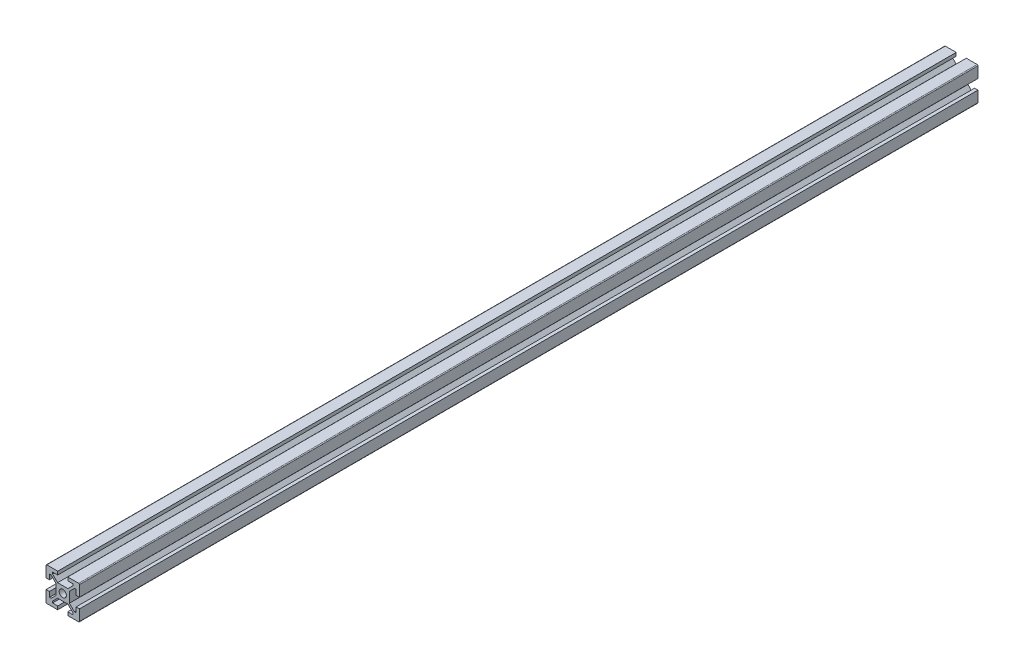
SolidWorks part; units mm, degrees
ref_plane "Front Plane" through (0, 0, 0) normal (0, 0, 1) x (1, 0, 0)
ref_plane "Top Plane" through (0, 0, 0) normal (0, 1, 0) x (1, 0, 0)
ref_plane "Right Plane" through (0, 0, 0) normal (1, 0, 0) x (0, 0, -1)
sketch "Sketch1" plane through (0, 0, 0) normal (0, 0, 1) x (1, 0, 0)
  line L0 (-3, 10) -> (-9.5, 10)
  line L1 (-10, 10) -> (10, 10) construction
  line L2 (-10, 10) -> (-10, -10) construction
  line L3 (-10, -10) -> (10, -10) construction
  line L4 (10, 10) -> (10, -10) construction
  line L5 (-10, 10) -> (10, -10) construction
  line L6 (-10, -10) -> (10, 10) construction
  line L7 (-8, 8) -> (8, 8) construction
  line L8 (-8, 8) -> (-8, -8) construction
  line L9 (-8, -8) -> (8, -8) construction
  line L10 (8, 8) -> (8, -8) construction
  line L11 (-8, 8) -> (8, -8) construction
  line L12 (-8, -8) -> (8, 8) construction
  line L13 (-4, 4) -> (4, 4) construction
  line L14 (-4, 4) -> (-4, -4) construction
  line L15 (-4, -4) -> (4, -4) construction
  line L16 (4, 4) -> (4, -4) construction
  line L17 (-4, 4) -> (4, -4) construction
  line L18 (-4, -4) -> (4, 4) construction
  line L19 (-3, 3) -> (3, 3) construction
  line L20 (-3, 3) -> (-3, -3) construction
  line L21 (-3, -3) -> (3, -3) construction
  line L22 (3, 3) -> (3, -3) construction
  line L23 (-3, 3) -> (3, -3) construction
  line L24 (-3, -3) -> (3, 3) construction
  line L25 (-10, 9.5) -> (-10, 3)
  line L26 (-10.4596, 9.5404) -> (9.5404, -10.4596) construction
  line L27 (-9.5404, -10.4596) -> (10.4596, 9.5404) construction
  line L28 (-9.5404, 10.4596) -> (10.4596, -9.5404) construction
  line L29 (-10.4596, -9.5404) -> (9.5404, 10.4596) construction
  line L30 (-10, 3) -> (-8, 3)
  line L31 (-8, 3) -> (-8, 6.0808)
  line L32 (-8, 6.0808) -> (-7, 6.0808)
  line L33 (-7, 6.0808) -> (-4, 3.0808)
  line L34 (-3, 10) -> (-3, 8)
  line L35 (-3, 8) -> (-6.0808, 8)
  line L36 (-6.0808, 8) -> (-6.0808, 7)
  line L37 (-6.0808, 7) -> (-3.0808, 4)
  line L38 (-3.0808, 4) -> (3.0808, 4)
  line L39 (3.0808, 4) -> (6.0808, 7)
  line L40 (6.0808, 7) -> (6.0808, 8)
  line L41 (6.0808, 8) -> (3, 8)
  line L42 (3, 8) -> (3, 10)
  line L43 (3, 10) -> (9.5, 10)
  line L44 (10, 9.5) -> (10, 3)
  line L45 (10, 3) -> (8, 3)
  line L46 (8, 3) -> (8, 6.0808)
  line L47 (8, 6.0808) -> (7, 6.0808)
  line L48 (7, 6.0808) -> (4, 3.0808)
  line L49 (4, 3.0808) -> (4, -3.0808)
  line L50 (4, -3.0808) -> (7, -6.0808)
  line L51 (7, -6.0808) -> (8, -6.0808)
  line L52 (8, -6.0808) -> (8, -3)
  line L53 (8, -3) -> (10, -3)
  line L54 (10, -3) -> (10, -9.5)
  line L55 (9.5, -10) -> (3, -10)
  line L56 (3, -10) -> (3, -8)
  line L57 (3, -8) -> (6.0808, -8)
  line L58 (6.0808, -8) -> (6.0808, -7)
  line L59 (6.0808, -7) -> (3.0808, -4)
  line L60 (3.0808, -4) -> (-3.0808, -4)
  line L61 (-3.0808, -4) -> (-6.0808, -7)
  line L62 (-6.0808, -7) -> (-6.0808, -8)
  line L63 (-6.0808, -8) -> (-3, -8)
  line L64 (-3, -8) -> (-3, -10)
  line L65 (-3, -10) -> (-9.5, -10)
  line L66 (-10, -9.5) -> (-10, -3)
  line L67 (-10, -3) -> (-8, -3)
  line L68 (-8, -3) -> (-8, -6.0808)
  line L69 (-8, -6.0808) -> (-7, -6.0808)
  line L70 (-7, -6.0808) -> (-4, -3.0808)
  line L71 (-4, -3.0808) -> (-4, 3.0808)
  circle A0 centre (0, 0) radius 2.15
  arc A1 (-9.5, -10) -> (-10, -9.5) centre (-9.5, -9.5) cw
  arc A2 (10, -9.5) -> (9.5, -10) centre (9.5, -9.5) cw
  arc A3 (9.5, 10) -> (10, 9.5) centre (9.5, 9.5) cw
  arc A4 (-9.5, 10) -> (-10, 9.5) centre (-9.5, 9.5) ccw
  point P0 (0, 0)
  point P6 (0, 0)
  dimension "D3" = 4.3
  dimension "D9" = 0.5
  dimension "D1" = 20
  dimension "D2" = 16
  dimension "D4" = 8
  dimension "D5" = 6
  dimension "D8" = 1
  dimension "D6" = 0.65
  dimension "D7" = 0.65
extrude "Boss-Extrude1" add sketch "Sketch1" along normal blind 537
